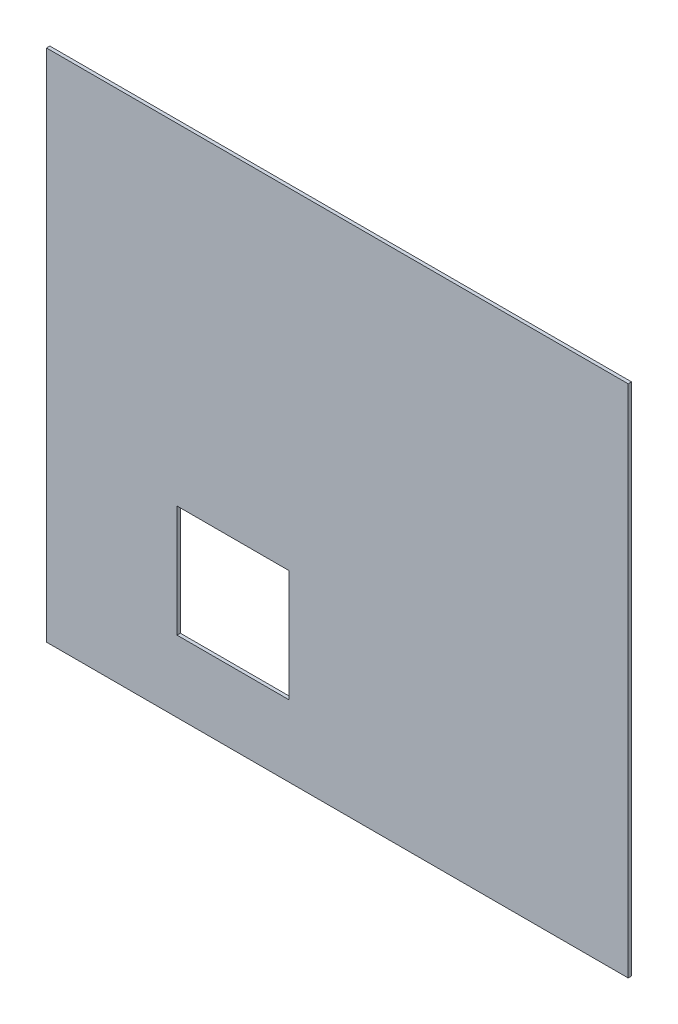
SolidWorks part; units mm, degrees
ref_plane "前视基准面" through (0, 0, 0) normal (0, 0, 1) x (1, 0, 0)
ref_plane "上视基准面" through (0, 0, 0) normal (0, 1, 0) x (1, 0, 0)
ref_plane "右视基准面" through (0, 0, 0) normal (1, 0, 0) x (0, 0, -1)
sketch "草图1" plane through (0, 0, 0) normal (0, 0, 1) x (1, 0, 0)
  line L1 (-260, 230) -> (260, 230)
  line L2 (-260, 230) -> (-260, -230)
  line L3 (-260, -230) -> (260, -230)
  line L4 (260, 230) -> (260, -230)
  line L5 (-260, 230) -> (260, -230) construction
  line L6 (-260, -230) -> (260, 230) construction
  point P0 (0, 0)
  dimension "D1" = 520
  dimension "D2" = 460
extrude "凸台-拉伸1" add sketch "草图1" along normal blind 3
sketch "草图2" plane through (0, 0, 3) normal (0, 0, 1) x (1, 0, 0)
  line L1 (-143.35, -66.2265) -> (-43.35, -66.2265)
  line L2 (-143.35, -66.2265) -> (-143.35, -166.2265)
  line L3 (-143.35, -166.2265) -> (-43.35, -166.2265)
  line L4 (-43.35, -66.2265) -> (-43.35, -166.2265)
  line L5 (-143.35, -66.2265) -> (-43.35, -166.2265) construction
  line L6 (-143.35, -166.2265) -> (-43.35, -66.2265) construction
  line L7 (260, -230) -> (260, 230) construction
  line L8 (260, 230) -> (-260, 230) construction
  point P0 (-93.35, -116.2265)
  dimension "D1" = 303.35
  dimension "D2" = 353.35
  dimension "D3" = 296.2265
extrude "切除-拉伸1" cut sketch "草图2" against normal blind 10
